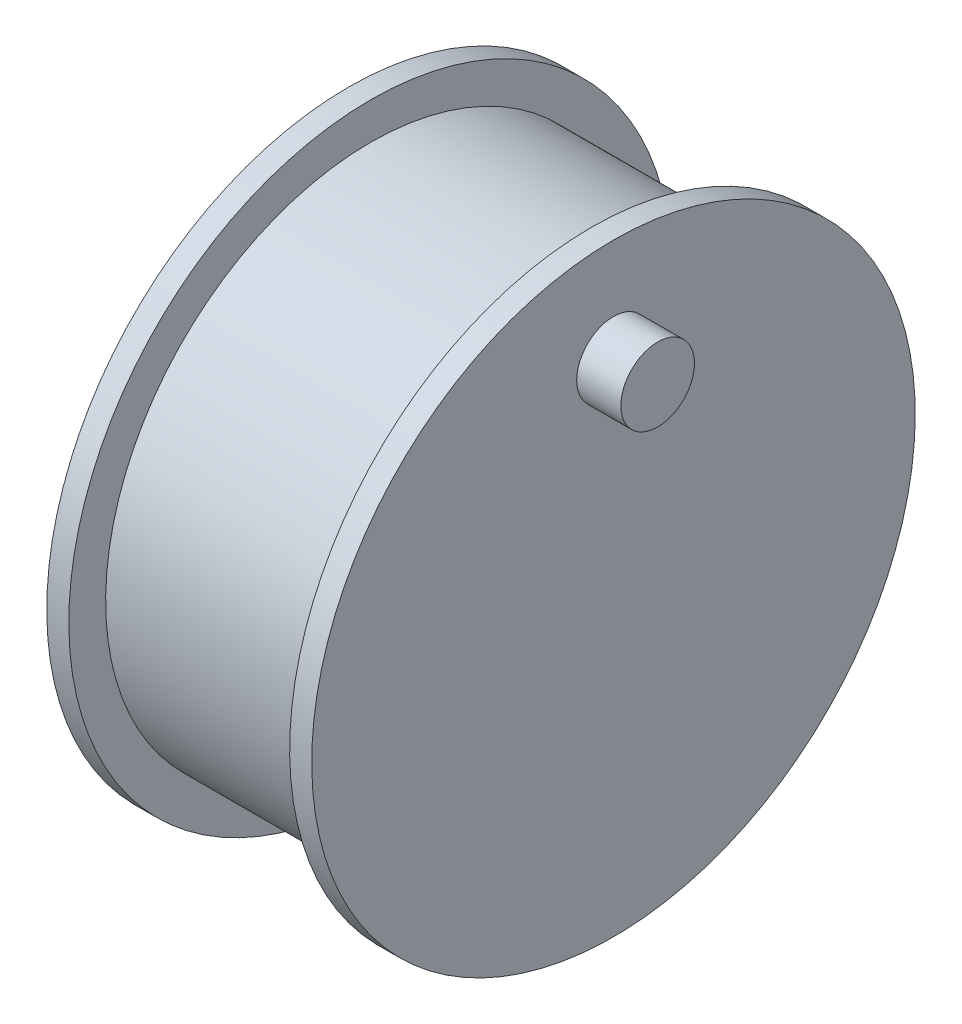
SolidWorks part; units mm, degrees
material "Alumina"
ref_plane "Front Plane" through (0, 0, 0) normal (0, 0, 1) x (1, 0, 0)
ref_plane "Top Plane" through (0, 0, 0) normal (0, 1, 0) x (1, 0, 0)
ref_plane "Right Plane" through (0, 0, 0) normal (1, 0, 0) x (0, 0, -1)
sketch "Sketch1" plane through (0, 0, 0) normal (0, 0, 1) x (1, 0, 0)
  line L0 (9, 0) -> (-9, 0)
  line L1 (-9, 0) -> (-9, 20.5)
  line L2 (-9, 20.5) -> (-7.5, 20.5)
  line L3 (-7.5, 20.5) -> (-7.5, 18)
  line L4 (-7.5, 18) -> (7.5, 18)
  line L5 (7.5, 18) -> (7.5, 20.5)
  line L6 (7.5, 20.5) -> (9, 20.5)
  line L7 (9, 20.5) -> (9, 0)
  dimension "D1" = 15
  dimension "D2" = 18
  dimension "D3" = 2.5
  dimension "D4" = 7.5
  dimension "D5" = 1.5
  dimension "D6" = 1.5
revolve "Revolve1" add sketch "Sketch1" angle 360 about L0
sketch "Sketch2" plane through (9, 0, 0) normal (1, 0, 0) x (0, 0, -1)
  line L0 (0, 0) -> (0, 13.5) construction
  circle A0 centre (0, 13.5) radius 2.5
  dimension "D2" = 5
  dimension "D1" = 13.5
extrude "Boss-Extrude1" add sketch "Sketch2" along normal blind 3
